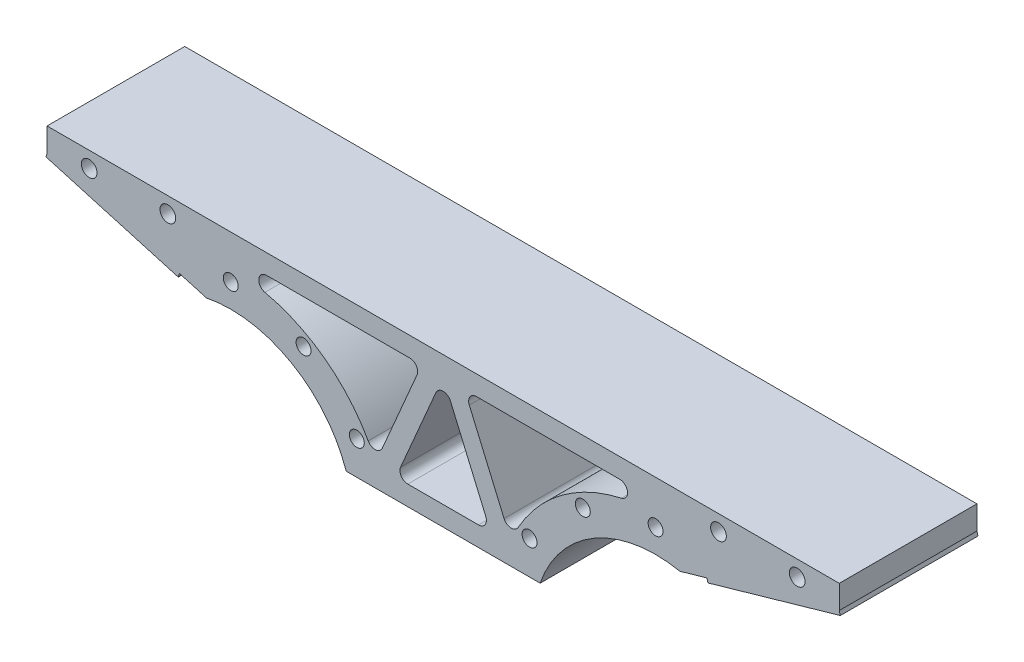
SolidWorks part; units mm, degrees
material "轻木"
ref_plane "前视基准面" through (0, 0, 0) normal (0, 0, 1) x (1, 0, 0)
ref_plane "上视基准面" through (0, 0, 0) normal (0, 1, 0) x (1, 0, 0)
ref_plane "右视基准面" through (0, 0, 0) normal (1, 0, 0) x (0, 0, -1)
sketch "草图1" plane through (0, 0, 0) normal (0, 0, 1) x (1, 0, 0)
  line L0 (-54, 0) -> (54, 0) construction
  line L1 (0, 0) -> (0, 10) construction
  line L2 (-46.42, 26.4347) -> (-100.7026, 42)
  line L3 (46.42, 26.4347) -> (100.7026, 42)
  line L4 (-28.3826, 10) -> (28.3826, 10)
  line L5 (-100.7026, 42) -> (-100.7026, 48)
  line L6 (-100.7026, 48) -> (100.7026, 48)
  line L7 (100.7026, 48) -> (100.7026, 42)
  line L8 (-90, 44) -> (-70, 44) construction
  line L9 (90, 44) -> (70, 44) construction
  circle A0 centre (-54, 0) radius 26.5 construction
  circle A1 centre (54, 0) radius 26.5 construction
  arc A2 (-28.3826, 10) -> (-46.42, 26.4347) centre (-54, 0) ccw
  arc A3 (28.3826, 10) -> (46.42, 26.4347) centre (54, 0) cw
  circle A4 centre (-54, 0) radius 37 construction
  circle A5 centre (-54, 37) radius 1.9
  circle A6 centre (-35.5, 32.0429) radius 1.9
  circle A7 centre (-21.9571, 18.5) radius 1.9
  circle A8 centre (-17, 0) radius 1.9 construction
  circle A9 centre (17, 0) radius 1.9 construction
  circle A10 centre (21.9571, 18.5) radius 1.9
  circle A11 centre (35.5, 32.0429) radius 1.9
  circle A12 centre (54, 37) radius 1.9
  circle A13 centre (54, 0) radius 37 construction
  circle A14 centre (-90, 44) radius 2
  circle A15 centre (-70, 44) radius 2
  circle A16 centre (70, 44) radius 2
  circle A17 centre (90, 44) radius 2
  point P2 (0, 0)
  dimension "D2" = 53
  dimension "D3" = 55
  dimension "D8" = 74
  dimension "D9" = 3.8
  dimension "D11" = 20
  dimension "D13" = 4
  dimension "D1" = 108
  dimension "D4" = 16
  dimension "D5" = 10
  dimension "D6" = 6
  dimension "D7" = 38
  dimension "D12" = 70
  dimension "D14" = 4
  dimension "D10" = 4
extrude "凸台-拉伸1" add sketch "草图1" along normal blind 35
sketch "草图2" plane through (0, 0, 35) normal (0, 0, 1) x (1, 0, 0)
  line L0 (-100.7026, 42) -> (-100.9783, 41.0387)
  line L1 (-100.9783, 41.0387) -> (-67.3341, 31.3914)
  line L2 (-67.3341, 31.3914) -> (-67.0585, 32.3527)
  line L3 (-100.7026, 42) -> (-46.42, 26.4347) construction
  line L4 (-67.0585, 32.3527) -> (-100.7026, 42)
  line L5 (0, 10) -> (0, 48) construction
  line L6 (-28.3826, 10) -> (28.3826, 10) construction
  line L7 (100.7026, 48) -> (-100.7026, 48) construction
  line L8 (67.0585, 32.3527) -> (100.7026, 42)
  line L9 (67.3341, 31.3914) -> (67.0585, 32.3527)
  line L10 (100.9783, 41.0387) -> (67.3341, 31.3914)
  line L11 (100.7026, 42) -> (100.9783, 41.0387)
  dimension "D1" = 1
  dimension "D2" = 35
extrude "凸台-拉伸2" add sketch "草图2" against normal up to surface (35 mm away) up to face at (0, 32.1362, 0)
sketch "草图3" plane through (0, 0, 35) normal (0, 0, 1) x (1, 0, 0)
  line L1 (-6.6417, 40.2101) -> (-15.4766, 19.6585)
  line L3 (-10.8374, 17.7899) -> (-1.8374, 38.7258)
  line L4 (1.8374, 38.7258) -> (10.8374, 17.7899)
  line L5 (9, 15) -> (-9, 15)
  line L6 (-44.8896, 43) -> (-8.4792, 43)
  line L7 (100.7026, 48) -> (-100.7026, 48) construction
  line L8 (-28.3826, 10) -> (28.3826, 10) construction
  line L9 (0, 15) -> (0, 10) construction
  line L10 (44.8896, 43) -> (8.4792, 43)
  line L11 (6.6417, 40.2101) -> (15.4766, 19.6585)
  circle A0 centre (-54, 0) radius 40 construction
  arc A1 (-45.3234, 39.0476) -> (-19.0609, 19.4746) centre (-54, 0) cw
  arc A2 (-45.3234, 39.0476) -> (-44.8896, 43) centre (-44.8896, 41) cw
  arc A3 (10.8374, 17.7899) -> (9, 15) centre (9, 17) cw
  arc A4 (-10.8374, 17.7899) -> (-9, 15) centre (-9, 17) ccw
  arc A5 (-1.8374, 38.7258) -> (1.8374, 38.7258) centre (0, 37.9359) cw
  arc A6 (-8.4792, 43) -> (-6.6417, 40.2101) centre (-8.4792, 41) cw
  arc A7 (-19.0609, 19.4746) -> (-15.4766, 19.6585) centre (-17.314, 20.4484) ccw
  arc A8 (45.3234, 39.0476) -> (44.8896, 43) centre (44.8896, 41) ccw
  arc A9 (45.3234, 39.0476) -> (19.0609, 19.4746) centre (54, 0) ccw
  arc A10 (8.4792, 43) -> (6.6417, 40.2101) centre (8.4792, 41) ccw
  arc A11 (19.0609, 19.4746) -> (15.4766, 19.6585) centre (17.314, 20.4484) cw
  point P10 (0, 15)
  point P25 (0, 43)
  dimension "D1" = 80
  dimension "D2" = 5
  dimension "D4" = 2
  dimension "D6" = 2
  dimension "D3" = 5
  dimension "D5" = 5
  dimension "D7" = 18
extrude "切除-拉伸1" cut sketch "草图3" against normal through all
sketch "草图4" plane through (0, 0, 0) normal (0, 0, -1) x (-1, 0, 0)
  line L0 (0, 0) -> (0, 48) construction
  line L1 (-100.7026, 48) -> (100.7026, 48) construction
  circle A0 centre (54, 0) radius 41.5
  circle A1 centre (-54, 0) radius 41.5
  dimension "D1" = 83
extrude "切除-拉伸2" cut sketch "草图4" against normal blind 5.5
sketch "草图5" plane through (0, 0, 5.5) normal (0, 0, -1) x (-1, 0, 0)
  circle A0 centre (-54, 0) radius 31
  circle A1 centre (54, 0) radius 31
  dimension "D1" = 62
extrude "切除-拉伸3" cut sketch "草图5" against normal through all
